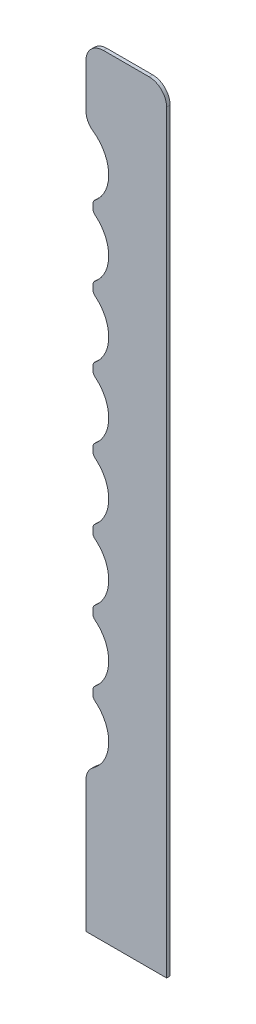
SolidWorks part; units mm, degrees
ref_plane "Front Plane" through (0, 0, 0) normal (0, 0, 1) x (1, 0, 0)
ref_plane "Top Plane" through (0, 0, 0) normal (0, 1, 0) x (1, 0, 0)
ref_plane "Right Plane" through (0, 0, 0) normal (1, 0, 0) x (0, 0, -1)
sketch "Sketch1" plane through (0, 0, 0) normal (0, 0, 1) x (1, 0, 0)
  line L0 (-4, 50) -> (-4, 70) construction
  line L1 (0, 0) -> (23, 0)
  line L2 (0, 0) -> (0, 37.3806)
  line L3 (5, 220) -> (18, 220)
  line L4 (23, 0) -> (23, 215)
  line L5 (0, 202.6194) -> (0, 215)
  line L13 (2, 199.7082) -> (2, 40.2918) construction
  line L14 (2, 59.3675) -> (2, 60.6325)
  line L15 (2, 79.3675) -> (2, 80.6325)
  line L16 (2, 99.3675) -> (2, 100.6325)
  line L17 (2, 119.3675) -> (2, 120.6325)
  line L18 (2, 139.3675) -> (2, 140.6325)
  line L19 (2, 179.3675) -> (2, 180.6325)
  line L20 (2, 159.3675) -> (2, 160.6325)
  arc A0 (2.0968, 41.4514) -> (2.5625, 58.1966) centre (-4, 50) ccw
  arc A1 (2.5625, 61.8034) -> (2.5625, 78.1966) centre (-4, 70) ccw
  arc A2 (2.5625, 81.8034) -> (2.5625, 98.1966) centre (-4, 90) ccw
  arc A3 (2.5625, 101.8034) -> (2.5625, 118.1966) centre (-4, 110) ccw
  arc A4 (2.5625, 121.8034) -> (2.5625, 138.1966) centre (-4, 130) ccw
  arc A5 (2.5625, 141.8034) -> (2.5625, 158.1966) centre (-4, 150) ccw
  arc A6 (2.5625, 161.8034) -> (2.5625, 178.1966) centre (-4, 170) ccw
  arc A7 (2.5625, 181.8034) -> (2.0968, 198.5486) centre (-4, 190) ccw
  arc A8 (2.5625, 61.8034) -> (2, 60.6325) centre (3.5, 60.6325) ccw
  arc A9 (2.5625, 58.1966) -> (2, 59.3675) centre (3.5, 59.3675) cw
  arc A10 (2.5625, 78.1966) -> (2, 79.3675) centre (3.5, 79.3675) cw
  arc A11 (2.5625, 81.8034) -> (2, 80.6325) centre (3.5, 80.6325) ccw
  arc A12 (2.5625, 98.1966) -> (2, 99.3675) centre (3.5, 99.3675) cw
  arc A13 (2.5625, 101.8034) -> (2, 100.6325) centre (3.5, 100.6325) ccw
  arc A14 (2.5625, 118.1966) -> (2, 119.3675) centre (3.5, 119.3675) cw
  arc A15 (2.5625, 121.8034) -> (2, 120.6325) centre (3.5, 120.6325) ccw
  arc A16 (2.5625, 138.1966) -> (2, 139.3675) centre (3.5, 139.3675) cw
  arc A17 (2.5625, 141.8034) -> (2, 140.6325) centre (3.5, 140.6325) ccw
  arc A18 (2.5625, 158.1966) -> (2, 159.3675) centre (3.5, 159.3675) cw
  arc A19 (2.5625, 161.8034) -> (2, 160.6325) centre (3.5, 160.6325) ccw
  arc A20 (2, 179.3675) -> (2.5625, 178.1966) centre (3.5, 179.3675) ccw
  arc A21 (2.5625, 181.8034) -> (2, 180.6325) centre (3.5, 180.6325) ccw
  arc A22 (18, 220) -> (23, 215) centre (18, 215) cw
  arc A23 (0, 215) -> (5, 220) centre (5, 215) cw
  arc A24 (2.0968, 198.5486) -> (0, 202.6194) centre (5, 202.6194) cw
  arc A25 (0, 37.3806) -> (2.0968, 41.4514) centre (5, 37.3806) cw
  point P30 (2, 61.3832)
  point P34 (2, 58.6168)
  point P41 (2, 78.6168)
  point P44 (2, 81.3832)
  point P47 (2, 98.6168)
  point P50 (2, 101.3832)
  point P53 (2, 118.6168)
  point P56 (2, 121.3832)
  point P59 (2, 138.6168)
  point P62 (2, 141.3832)
  point P65 (2, 158.6168)
  point P68 (2, 161.3832)
  point P71 (2, 178.6168)
  point P74 (2, 181.3832)
  point P79 (0, 220)
  point P82 (0, 199.7082)
  point P85 (0, 40.2918)
  dimension "D3" = 21
  dimension "D9" = 1.5
  dimension "D10" = 5
  dimension "D1" = 220
  dimension "D2" = 23
  dimension "D4" = 50
  dimension "D5" = 4
  dimension "D7" = 20
  dimension "D8" = 21
  dimension "D6" = 8
extrude "Boss-Extrude1" add sketch "Sketch1" along normal blind 1 contours L4 A22 L3 A23 L5 A24 A7 A21 L19 A20 A6 A19 L20 A18 A5 A17 L18 A16 A4 A15 L17 A14 A3 A13 L16 A12 A2 A11 L15 A10 A1 A8 L14 A9 A0 A25 L2 L1
